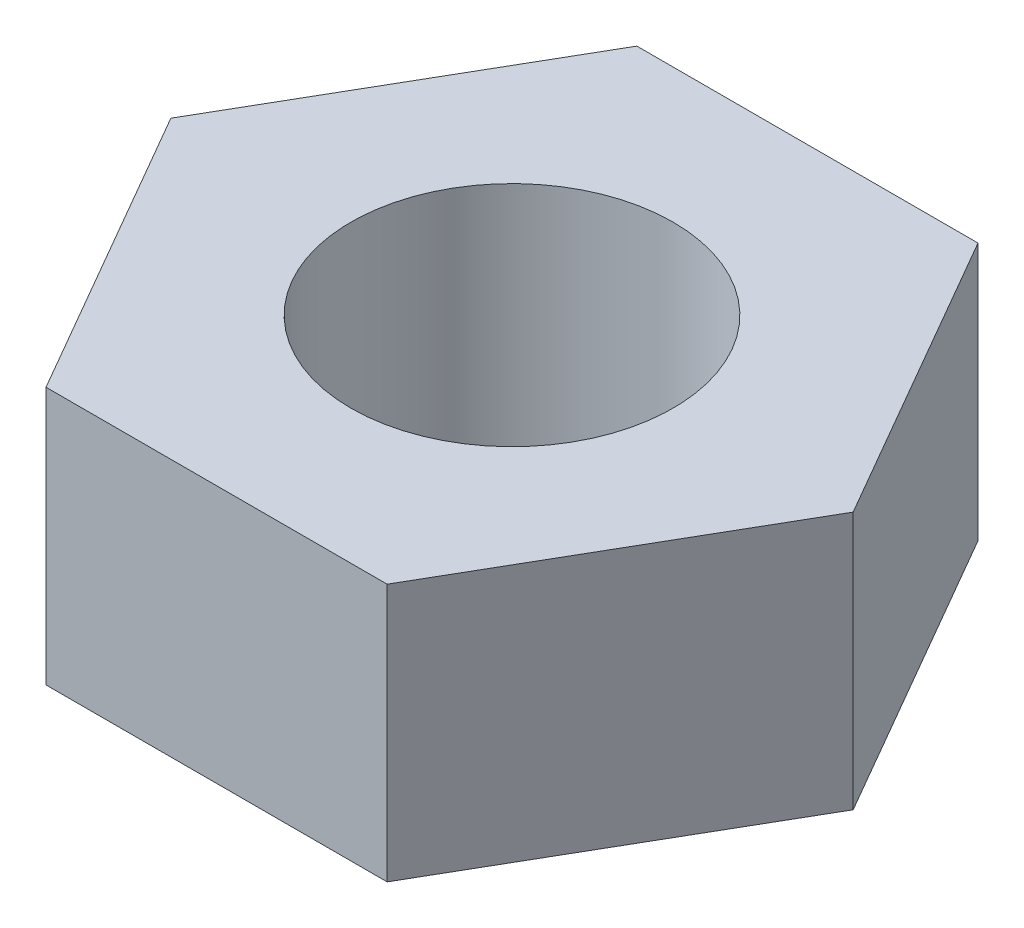
SolidWorks part; units mm, degrees
ref_plane "Front Plane" through (0, 0, 0) normal (0, 0, 1) x (1, 0, 0)
ref_plane "Top Plane" through (0, 0, 0) normal (0, 1, 0) x (1, 0, 0)
ref_plane "Right Plane" through (0, 0, 0) normal (1, 0, 0) x (0, 0, -1)
sketch "Sketch1" plane through (0, 0, 0) normal (0, 1, 0) x (1, 0, 0)
  line L1 (3.1754, 0) -> (1.5877, 2.75)
  line L2 (1.5877, 2.75) -> (-1.5877, 2.75)
  line L3 (-1.5877, 2.75) -> (-3.1754, 0)
  line L4 (-3.1754, 0) -> (-1.5877, -2.75)
  line L5 (-1.5877, -2.75) -> (1.5877, -2.75)
  line L6 (1.5877, -2.75) -> (3.1754, 0)
  circle A0 centre (0, 0) radius 2.75 construction
  circle A1 centre (0, 0) radius 1.5
  dimension "D2" = 3
  dimension "D1" = 5.5
extrude "Boss-Extrude1" add sketch "Sketch1" along normal blind 2.4
